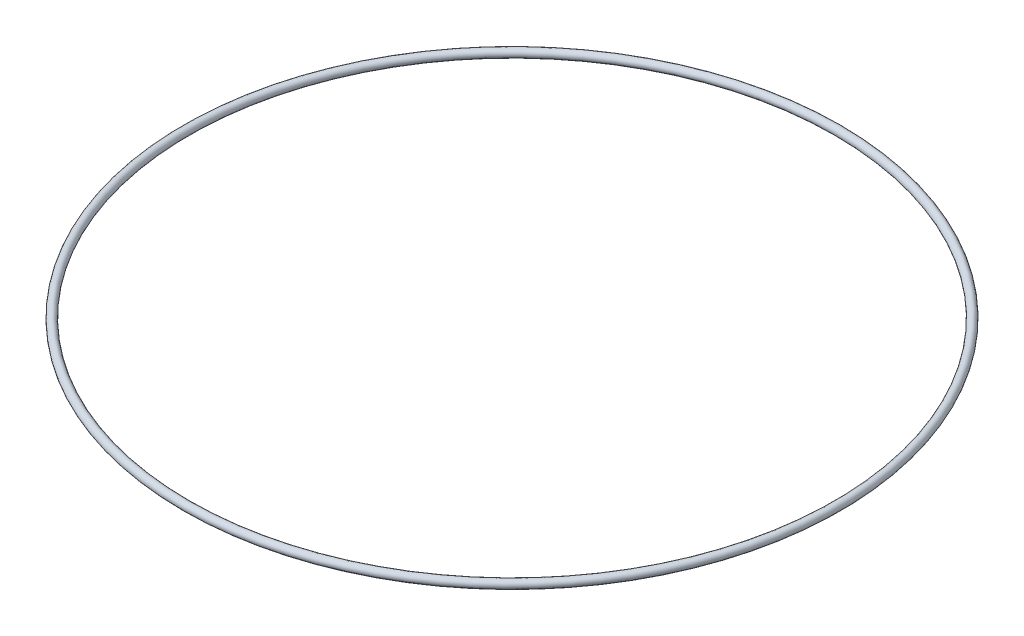
SolidWorks part; units mm, degrees
ref_plane "Plan de face" through (0, 0, 0) normal (0, 0, 1) x (1, 0, 0)
ref_plane "Plan de dessus" through (0, 0, 0) normal (0, 1, 0) x (1, 0, 0)
ref_plane "Plan de droite" through (0, 0, 0) normal (1, 0, 0) x (0, 0, -1)
sketch "Esquisse1" plane through (0, 0, 0) normal (0, 0, 1) x (1, 0, 0)
  line L0 (0, 0) -> (0, 7.567) construction
  circle A0 centre (-19.75, 0) radius 0.25
  dimension "D1" = 0.5
  dimension "D2" = 19.75
revolve "Révolution1" add sketch "Esquisse1" angle 360 about L0
